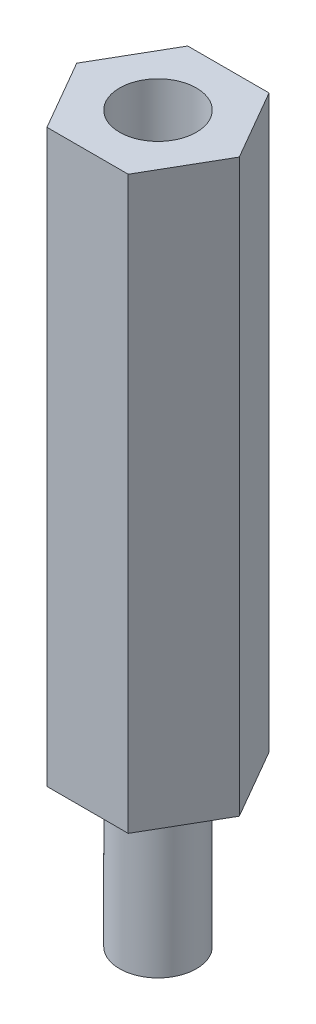
SolidWorks part; units mm, degrees
ref_plane "Plan de face" through (0, 0, 0) normal (0, 0, 1) x (1, 0, 0)
ref_plane "Plan de dessus" through (0, 0, 0) normal (0, 1, 0) x (1, 0, 0)
ref_plane "Plan de droite" through (0, 0, 0) normal (1, 0, 0) x (0, 0, -1)
sketch "Esquisse1" plane through (0, 0, 0) normal (0, 1, 0) x (1, 0, 0)
  line L0 (-3.1754, 0) -> (3.1754, 0) construction
  line L1 (1.5877, 2.75) -> (-1.5877, 2.75)
  line L2 (-1.5877, 2.75) -> (-3.1754, 0)
  line L3 (-3.1754, 0) -> (-1.5877, -2.75)
  line L4 (-1.5877, -2.75) -> (1.5877, -2.75)
  line L5 (1.5877, -2.75) -> (3.1754, 0)
  line L6 (3.1754, 0) -> (1.5877, 2.75)
  circle A0 centre (0, 0) radius 2.75 construction
  circle A1 centre (0, 0) radius 1.5
  dimension "D2" = 3
  dimension "D1" = 5.5
extrude "Boss.-Extru.1" add sketch "Esquisse1" along normal blind 22.3
sketch "Esquisse2" plane through (0, 0, 0) normal (0, -1, 0) x (1, 0, 0)
  circle A0 centre (0, 0) radius 1.5
  dimension "D1" = 3
extrude "Boss.-Extru.2" add sketch "Esquisse2" along normal blind 6 and the other way blind 1
